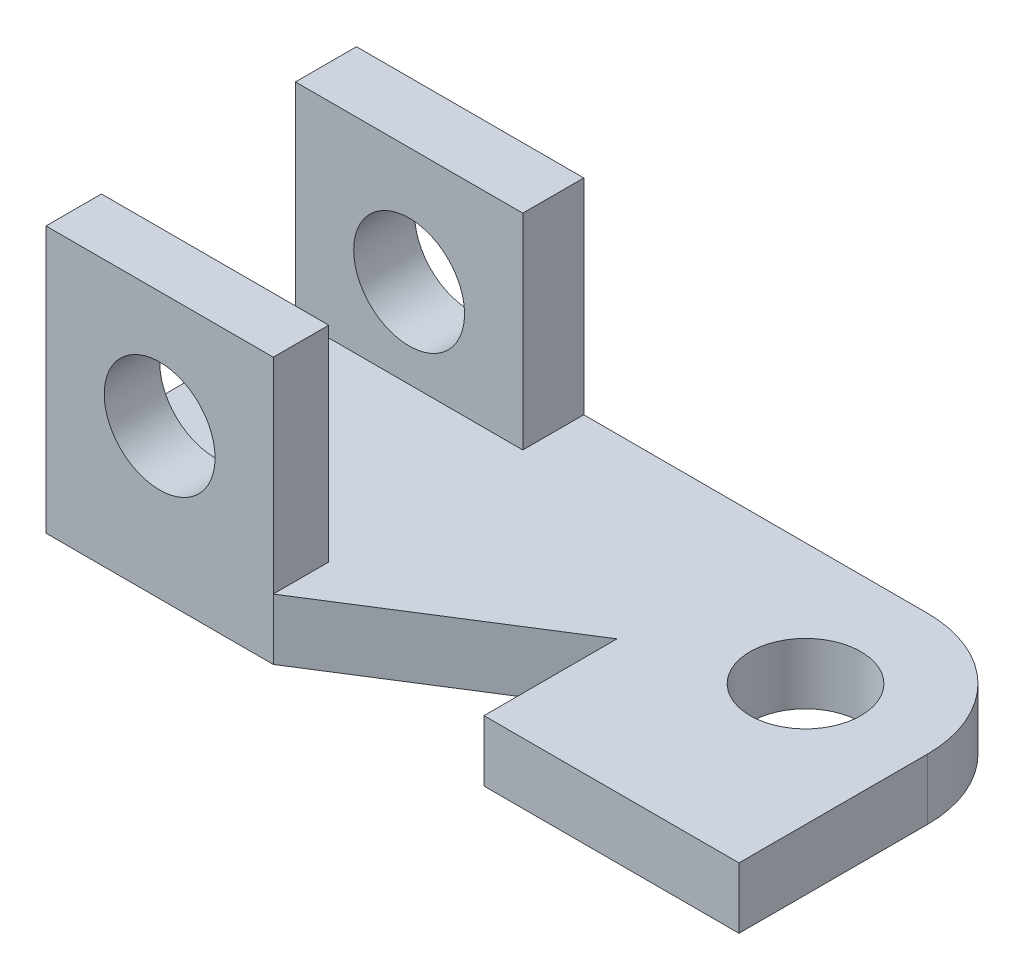
SolidWorks part; units mm, degrees
ref_plane "Front Plane" through (0, 0, 0) normal (0, 0, 1) x (1, 0, 0)
ref_plane "Top Plane" through (0, 0, 0) normal (0, 1, 0) x (1, 0, 0)
ref_plane "Right Plane" through (0, 0, 0) normal (1, 0, 0) x (0, 0, -1)
sketch "Sketch1" plane through (0, 0, 0) normal (0, 1, 0) x (1, 0, 0)
  line L0 (0, 0) -> (-46, 0)
  line L1 (-46, 0) -> (-46, 24)
  line L2 (-46, 24) -> (-84, 0)
  line L3 (-84, 0) -> (-125, 0)
  line L4 (-125, 0) -> (-125, 56)
  line L5 (-125, 56) -> (-22, 56)
  line L6 (0, 34) -> (0, 0)
  arc A0 (-22, 56) -> (0, 34) centre (-22, 34) cw
  circle A1 centre (-22, 34) radius 10
  dimension "D5" = 22
  dimension "D7" = 20
  dimension "D1" = 56
  dimension "D2" = 125
  dimension "D3" = 38
  dimension "D4" = 24
  dimension "D6" = 41
extrude "Boss-Extrude1" add sketch "Sketch1" along normal blind 11
sketch "Sketch3" plane through (0, 11, 0) normal (0, 1, 0) x (1, 0, 0)
  line L0 (-125, 0) -> (-84, 0)
  line L1 (-84, 0) -> (-84, 10)
  line L2 (-84, 10) -> (-125, 10)
  line L3 (-125, 56) -> (-125, 0) construction
  line L4 (-125, 10) -> (-125, 0)
  dimension "D1" = 10
extrude "Boss-Extrude2" add sketch "Sketch3" along normal blind 37
sketch "Sketch4" plane through (0, 0, 0) normal (0, 0, 1) x (1, 0, 0)
  line L0 (-125, 0) -> (-84, 0) construction
  line L1 (-125, 48) -> (-125, 0) construction
  circle A0 centre (-104.5, 27) radius 10
  point P4 (0, 0)
  point P6 (-119.7572, 17.5867)
  dimension "D3" = 20
  dimension "D1" = 27
  dimension "D2" = 20.5
extrude "Cut-Extrude1" cut sketch "Sketch4" against normal blind 37
sketch "Sketch5" plane through (0, 0, -56) normal (0, 0, -1) x (-1, 0, 0)
  line L0 (84, 11) -> (125, 11)
  line L1 (22, 11) -> (125, 11) construction
  line L2 (84, 11) -> (125, 11) construction
  line L3 (125, 11) -> (125, 48)
  line L4 (125, 48) -> (84, 48)
  line L5 (84, 48) -> (125, 48) construction
  line L6 (84, 48) -> (84, 11)
  circle A0 centre (104.5, 27) radius 10
extrude "Boss-Extrude3" add sketch "Sketch5" against normal blind 11
